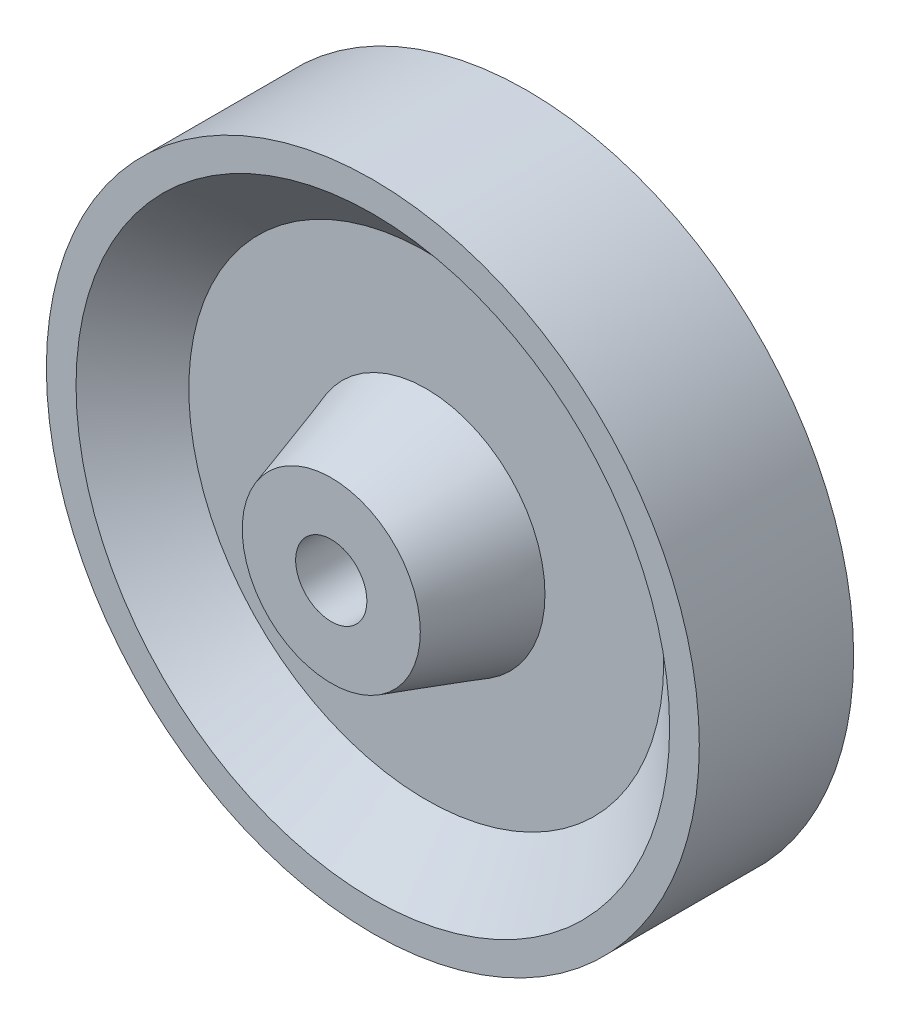
SolidWorks part; units mm, degrees
ref_plane "Front Plane" through (0, 0, 0) normal (0, 0, 1) x (1, 0, 0)
ref_plane "Top Plane" through (0, 0, 0) normal (0, 1, 0) x (1, 0, 0)
ref_plane "Right Plane" through (0, 0, 0) normal (1, 0, 0) x (0, 0, -1)
sketch "Sketch1" plane through (0, 0, 0) normal (1, 0, 0) x (0, 0, -1)
  line L0 (13, 55) -> (13, 50)
  line L1 (13, 50) -> (4, 40)
  line L2 (4, 40) -> (4, 20)
  line L3 (4, 20) -> (20, 15)
  line L4 (20, 15) -> (20, 6)
  line L5 (0, 55) -> (0, -55) construction
  line L6 (-20, 15) -> (-20, 6)
  line L7 (-4, 20) -> (-20, 15)
  line L8 (-4, 40) -> (-4, 20)
  line L9 (-13, 50) -> (-4, 40)
  line L10 (-13, 55) -> (-13, 50)
  line L11 (-13, 55) -> (13, 55)
  line L12 (-20, 6) -> (20, 6)
  line L13 (0, 0) -> (110.241, 0) construction
  dimension "D1" = 6
  dimension "D2" = 15
  dimension "D3" = 20
  dimension "D4" = 40
  dimension "D5" = 50
  dimension "D6" = 55
  dimension "D7" = 26
  dimension "D8" = 8
  dimension "D9" = 40
revolve "Revolve1" add sketch "Sketch1" angle 360 about L13
